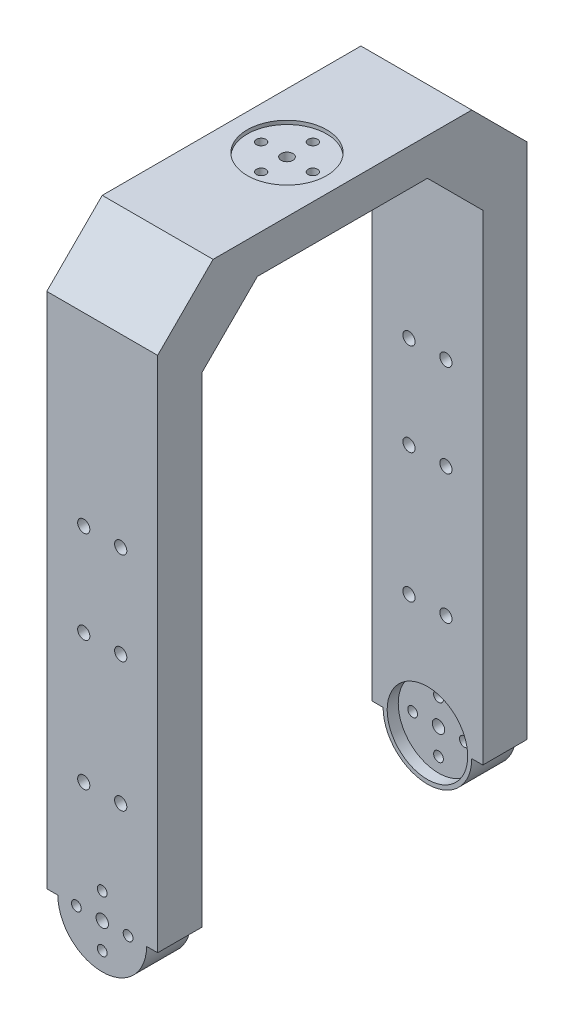
SolidWorks part; units mm, degrees
ref_plane "前视基准面" through (0, 0, 0) normal (0, 0, 1) x (1, 0, 0)
ref_plane "上视基准面" through (0, 0, 0) normal (0, 1, 0) x (1, 0, 0)
ref_plane "右视基准面" through (0, 0, 0) normal (1, 0, 0) x (0, 0, -1)
ref_plane "基准面4" through (0, 0, 38) normal (0, 0, 1) x (1, 0, 0)
sketch "草图1" plane through (0, 0, 38) normal (0, 0, 1) x (1, 0, 0)
  line L0 (-15, 145) -> (-15, 0)
  line L1 (-15, 145) -> (15, 145)
  line L2 (-15, 0) -> (15, 0)
  line L3 (15, 145) -> (15, 0)
  line L4 (-15, 145) -> (15, 0) construction
  line L5 (-15, 0) -> (15, 145) construction
  circle A0 centre (0, 0) radius 12
  point P3 (0, 0)
  point P4 (0, 72.5)
  dimension "D1" = 24
  dimension "D2" = 15
  dimension "D3" = 145
extrude "凸台-拉伸1" add sketch "草图1" along normal blind 12 contours A0 L2 L3 L1 L0 | L2 A0 | L2 A0
sketch "草图2" plane through (0, 145, 0) normal (0, 1, 0) x (1, 0, 0)
  line L1 (-15, -50) -> (15, -50)
  line L2 (-15, -50) -> (-15, 0)
  line L3 (-15, 0) -> (15, 0)
  line L4 (15, -50) -> (15, 0)
extrude "凸台-拉伸2" add sketch "草图2" along normal blind 10
sketch "草图3" plane through (0, 0, 38) normal (0, 0, -1) x (-1, 0, 0)
  circle A0 centre (0, 0) radius 10.9
  dimension "D1" = 21.8
extrude "切除-拉伸1" cut sketch "草图3" against normal blind 3
sketch "草图4" plane through (0, 0, 41) normal (0, 0, -1) x (-1, 0, 0)
  circle A0 centre (0, 0) radius 1.675
  dimension "D1" = 3.35
extrude "切除-拉伸2" cut sketch "草图4" against normal mid plane 36
mirror "镜向1" about plane through (0, 0, 0) normal (0, 0, 1) of "凸台-拉伸2"
mirror "镜向2" about plane through (0, 0, 0) normal (0, 0, 1) of "切除-拉伸1", "凸台-拉伸1", "切除-拉伸2"
chamfer "倒角1" distance 15 angle 45 4 edges at (0, 155, 50) (0, 155, -50) (0, 145, -38) (0, 145, 38)
sketch "草图5" plane through (0, 155, 0) normal (0, 1, 0) x (1, 0, 0)
  circle A0 centre (0, 0) radius 10.75
  dimension "D1" = 21.5
sketch "草图7" plane through (0, 145, 0) normal (0, -1, 0) x (1, 0, 0)
  circle A0 centre (0, 0) radius 10.5
extrude "切除-拉伸3" cut sketch "草图5" against normal blind 1
sketch "草图8" plane through (0, 154, 0) normal (0, 1, 0) x (1, 0, 0)
  circle A0 centre (0, 0) radius 1.6
  dimension "D1" = 3.2
extrude "切除-拉伸4" cut sketch "草图8" against normal blind 14
sketch "草图9" plane through (0, 0, 50) normal (0, 0, 1) x (1, 0, 0)
  circle A0 centre (-7, 0) radius 1.325
  circle A1 centre (0, 7) radius 1.325
  circle A2 centre (7, 0) radius 1.325
  circle A3 centre (0, -7) radius 1.325
  point P12 (0, 0)
  dimension "D1" = 2.65
  dimension "D2" = 7
  dimension "D3" = 4
extrude "切除-拉伸5" cut sketch "草图9" against normal blind 120
sketch "草图10" plane through (0, 155, 0) normal (0, 1, 0) x (1, 0, 0)
  circle A0 centre (-7, 0) radius 1.275
  circle A1 centre (0, 0) radius 1.6 construction
  circle A2 centre (0, 7) radius 1.275
  circle A3 centre (7, 0) radius 1.275
  circle A4 centre (0, -7) radius 1.275
  point P13 (0, 0)
  dimension "D1" = 2.55
  dimension "D2" = 7
  dimension "D3" = 4
extrude "切除-拉伸6" cut sketch "草图10" against normal blind 120
sketch "草图11" plane through (0, 0, 50) normal (0, 0, 1) x (1, 0, 0)
  line L0 (0, -55) -> (0, 55) construction
  line L1 (12, 0) -> (15, 0) construction
  circle A0 centre (-5, 30) radius 1.65
  circle A1 centre (5, 30) radius 1.65
  circle A2 centre (-5, 90) radius 1.65
  circle A3 centre (5, 90) radius 1.65
  dimension "D1" = 10
  dimension "D2" = 30
  dimension "D4" = 3.3
  dimension "D3" = 2
extrude "切除-拉伸7" cut sketch "草图11" against normal blind 130
sketch "草图12" plane through (0, 0, 50) normal (0, 0, 1) x (1, 0, 0)
  line L0 (0, -55) -> (0, 55) construction
  circle A3 centre (-5, 65) radius 1.65
  circle A4 centre (5, 65) radius 1.65
  dimension "D1" = 3.3
  dimension "D2" = 10
  dimension "D3" = 65
extrude "切除-拉伸8" cut sketch "草图12" against normal blind 120
